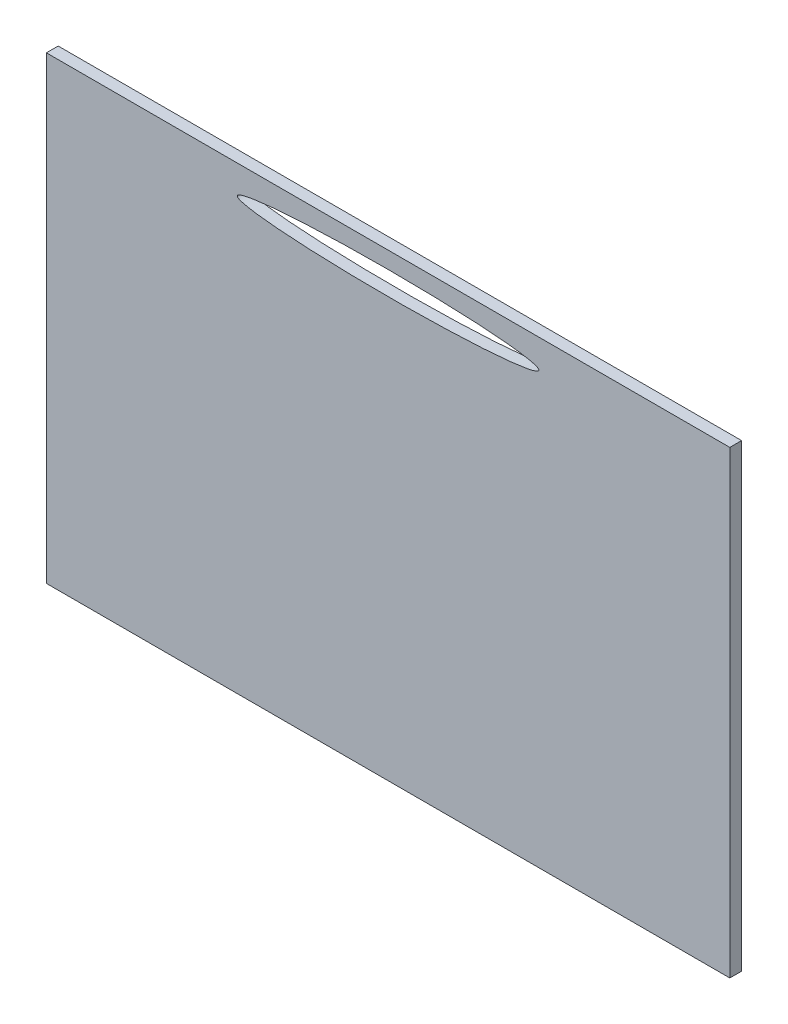
SolidWorks part; units mm, degrees
ref_plane "Alzado" through (0, 0, 0) normal (0, 0, 1) x (1, 0, 0)
ref_plane "Planta" through (0, 0, 0) normal (0, 1, 0) x (1, 0, 0)
ref_plane "Vista lateral" through (0, 0, 0) normal (1, 0, 0) x (0, 0, -1)
sketch "Croquis1" plane through (0, 0, 0) normal (0, 0, 1) x (1, 0, 0)
  line L0 (-57.75, 70) -> (58, 70) construction
  line L1 (-58, 2) -> (58, 2)
  line L2 (-58, 2) -> (-58, 80)
  line L3 (-58, 80) -> (58, 80)
  line L4 (58, 2) -> (58, 80)
  dimension "D1" = 10
extrude "Saliente-Extruir1" add sketch "Croquis1" along normal blind 2 contours L3 L4 L1 L2
sketch "Croquis2" plane through (0, 0, 2) normal (0, 0, 1) x (1, 0, 0)
  line L0 (0, 0) -> (0, 92.8753) construction
  ellipse E0 centre (0, 75.1534) end of major axis (25.5978, 75.1534) minor radius 2
  dimension "D1" = 2
extrude "Cortar-Extruir1" cut sketch "Croquis2" against normal up to next
